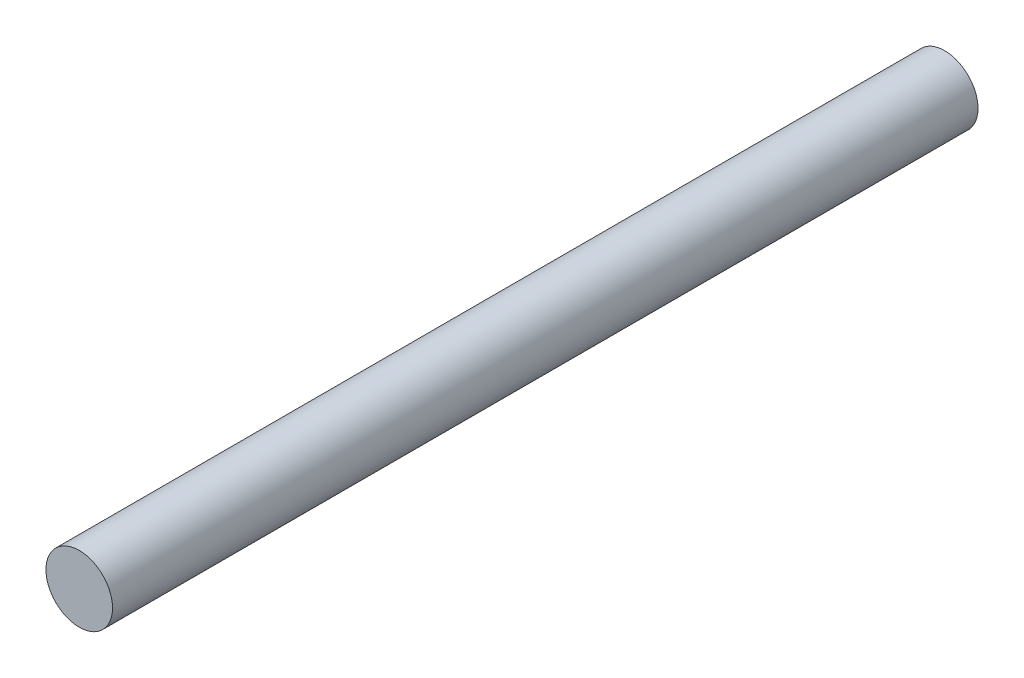
SolidWorks part; units mm, degrees
ref_plane "Plan de face" through (0, 0, 0) normal (0, 0, 1) x (1, 0, 0)
ref_plane "Plan de dessus" through (0, 0, 0) normal (0, 1, 0) x (1, 0, 0)
ref_plane "Plan de droite" through (0, 0, 0) normal (1, 0, 0) x (0, 0, -1)
sketch "Esquisse2" plane through (0, 0, 0) normal (0, 0, 1) x (1, 0, 0)
  circle A0 centre (0, 0) radius 3
  dimension "D1" = 6
extrude "Boss.-Extru.1" add sketch "Esquisse2" along normal blind 78
